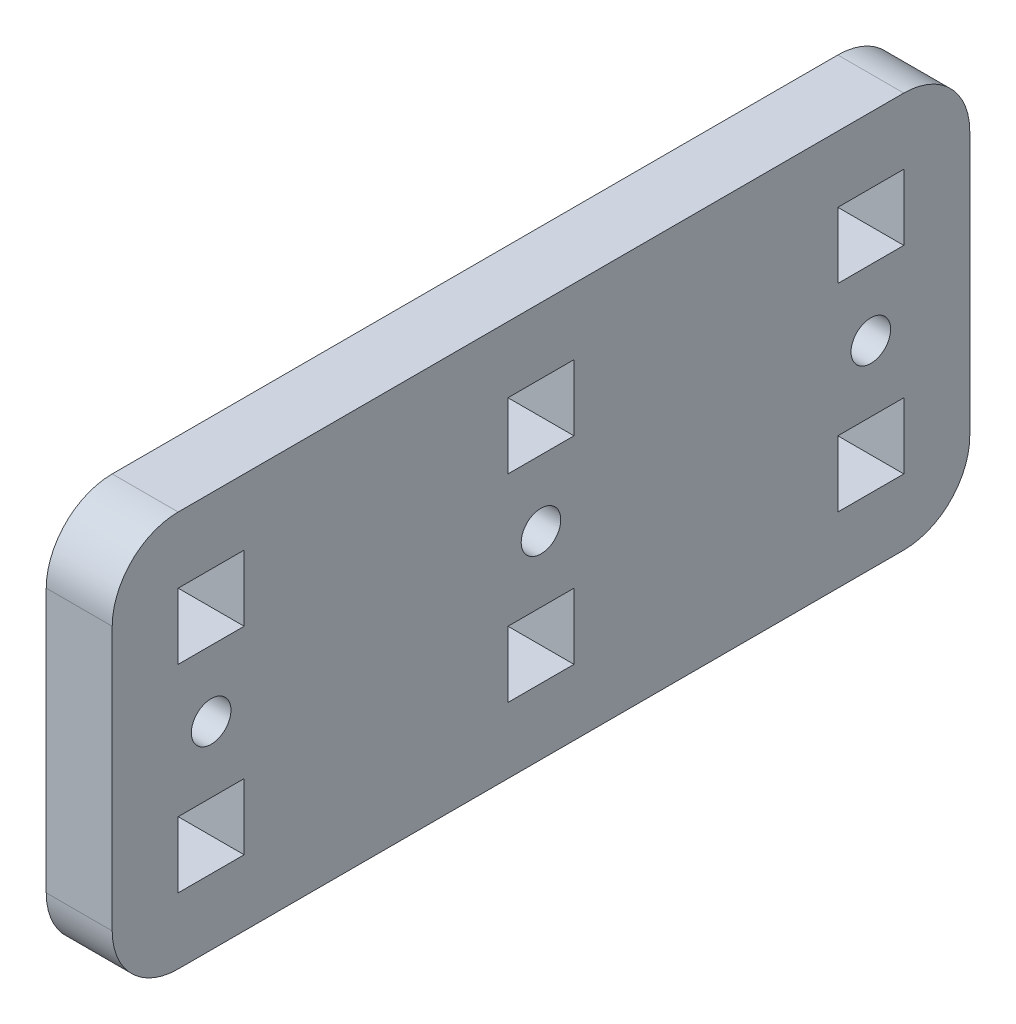
SolidWorks part; units mm, degrees
ref_plane "Front Plane" through (0, 0, 0) normal (0, 0, 1) x (1, 0, 0)
ref_plane "Top Plane" through (0, 0, 0) normal (0, 1, 0) x (1, 0, 0)
ref_plane "Right Plane" through (0, 0, 0) normal (1, 0, 0) x (0, 0, -1)
sketch "Sketch1" plane through (0, 0, 0) normal (1, 0, 0) x (0, 0, -1)
  line L0 (0, 15) -> (65, 15) construction
  line L1 (0, 0) -> (65, 0)
  line L2 (0, 0) -> (0, 30)
  line L3 (0, 30) -> (65, 30)
  line L4 (65, 0) -> (65, 30)
  line L5 (32.5, 30) -> (32.5, 0) construction
  line B0 (7.5, 20) -> (7.5, 10) construction
  line B1 (10, 20) -> (10, 25)
  line B2 (10, 20) -> (5, 20)
  line B3 (5, 20) -> (5, 25)
  line B4 (10, 25) -> (5, 25)
  line B5 (10, 10) -> (10, 5)
  line B6 (10, 10) -> (5, 10)
  line B7 (5, 10) -> (5, 5)
  line B8 (10, 5) -> (5, 5)
  line B9 (7.5, 15) -> (14.4724, 15) construction
  circle B10 centre (7.5, 15) radius 1.5
  line B11 (57.5, 20) -> (57.5, 10) construction
  line B12 (55, 20) -> (55, 25)
  line B13 (55, 20) -> (60, 20)
  line B14 (60, 20) -> (60, 25)
  line B15 (55, 25) -> (60, 25)
  line B16 (55, 10) -> (55, 5)
  line B17 (55, 10) -> (60, 10)
  line B18 (60, 10) -> (60, 5)
  line B19 (55, 5) -> (60, 5)
  circle B20 centre (57.5, 15) radius 1.5
  line B21 (32.5, 20) -> (32.5, 10) construction
  line B22 (30, 20) -> (30, 25)
  line B23 (30, 20) -> (35, 20)
  line B24 (35, 20) -> (35, 25)
  line B25 (30, 25) -> (35, 25)
  line B26 (30, 10) -> (30, 5)
  line B27 (30, 10) -> (35, 10)
  line B28 (35, 10) -> (35, 5)
  line B29 (30, 5) -> (35, 5)
  line B30 (32.5, 15) -> (25.5276, 15) construction
  circle B31 centre (32.5, 15) radius 1.5
  dimension "D1" = 5
  dimension "D2" = 5
  dimension "D3" = 50
sketch_block_instance "Trou M3 plots 5mm-1"
sketch_block "Trou M3 plots 5mm" parameters "D2"=3, "D1"=5, "D3"=5, "D4"=10
sketch_block_instance "Trou M3 plots 5mm-3"
sketch_block_instance "Trou M3 plots 5mm-2"
extrude "Boss-Extrude1" add sketch "Sketch1" along normal blind 5
fillet "Fillet1" radius 5 4 edges at (2.5, 0, -65) (2.5, 30, -65) (2.5, 0, 0) (2.5, 30, 0)
